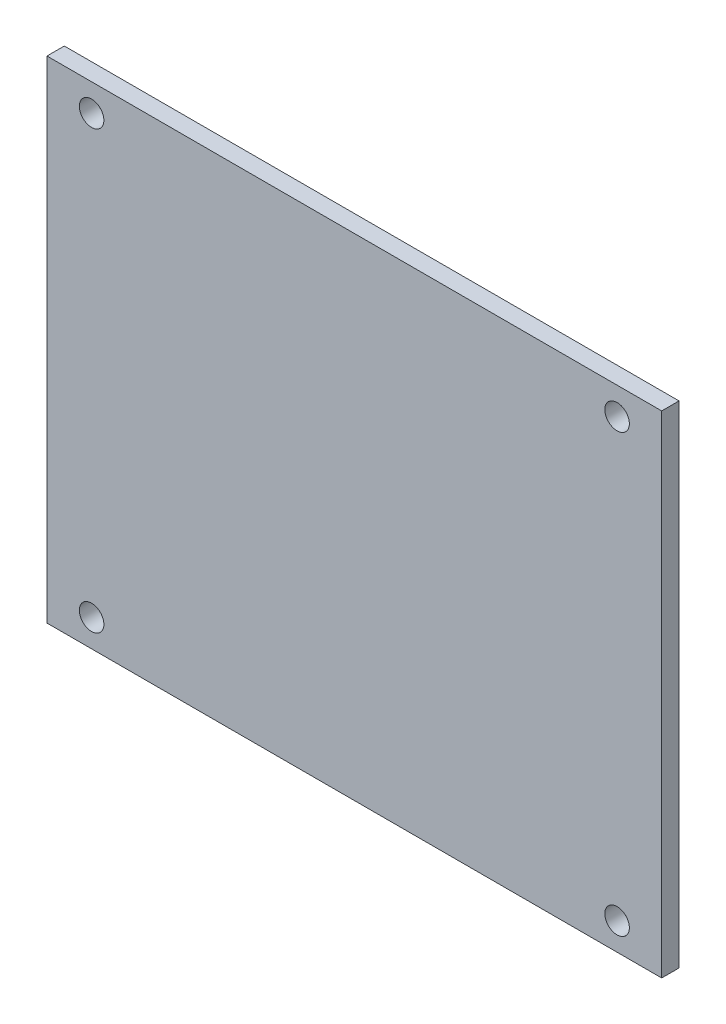
SolidWorks part; units mm, degrees
ref_plane "Front Plane" through (0, 0, 0) normal (0, 0, 1) x (1, 0, 0)
ref_plane "Top Plane" through (0, 0, 0) normal (0, 1, 0) x (1, 0, 0)
ref_plane "Right Plane" through (0, 0, 0) normal (1, 0, 0) x (0, 0, -1)
sketch "Sketch1" plane through (0, 0, 0) normal (0, 0, 1) x (1, 0, 0)
  line L1 (-56.325, -45) -> (56.325, -45)
  line L2 (-56.325, -45) -> (-56.325, 45)
  line L3 (-56.325, 45) -> (56.325, 45)
  line L4 (56.325, -45) -> (56.325, 45)
  line L5 (-56.325, -45) -> (56.325, 45) construction
  line L6 (-56.325, 45) -> (56.325, -45) construction
  point P0 (0, 0)
  dimension "D1" = 112.65
  dimension "D2" = 90
extrude "Boss-Extrude1" add sketch "Sketch1" along normal blind 3.175
hole_wizard "M4 Clearance Hole1" positions "Sketch2" profile "Sketch3" hole size "M4" standard "ANSI Metric" end condition through all
sketch "Sketch2" plane through (0, 0, 3.175) normal (0, 0, 1) x (1, 0, 0)
  line L0 (-56.325, 45) -> (-56.325, -45) construction
  line L1 (-56.325, -45) -> (56.325, -45) construction
  point P0 (-48.15, -40)
  dimension "D1" = 8.175
  dimension "D2" = 5
sketch "Sketch3" plane through (-48.15, -40, 3.175) normal (1, 0, 0) x (0, -1, 0)
  line L0 (0, 0) -> (0, 3.175)
  line L1 (0, 3.175) -> (2.25, 3.175)
  line L2 (2.25, 3.175) -> (2.25, 0)
  line L5 (2.25, 0) -> (0, 0)
  line L11 (0, -6.35) -> (0, 107.95) construction
  dimension "Thru Hole Dia." = 4.5
  dimension "Thru Hole Depth" = 3.175
mirror "Mirror1" about plane through (0, 0, 0) normal (1, 0, 0) of "M4 Clearance Hole1" second plane through (0, 0, 0) second plane normal (0, 1, 0)
